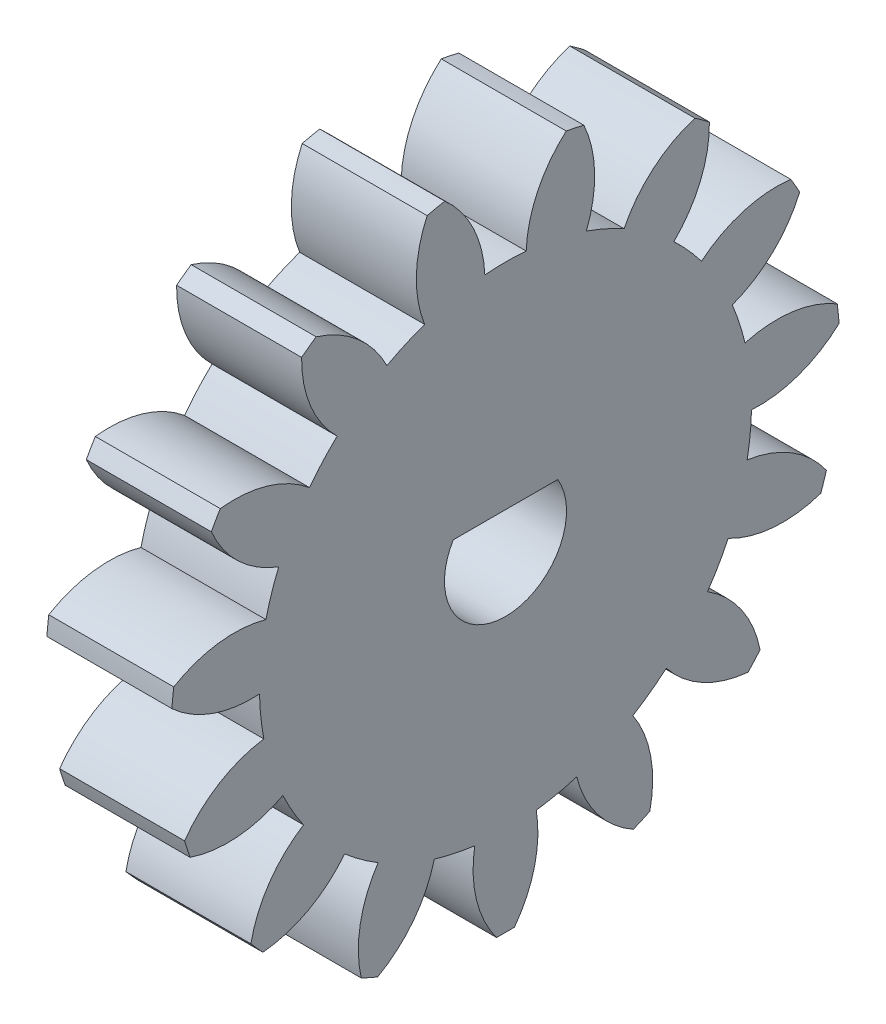
SolidWorks part; units mm, degrees
ref_plane "Plane1" through (0, 0, 0) normal (0, 0, 1) x (1, 0, 0)
ref_plane "Plane2" through (0, 0, 0) normal (0, 1, 0) x (1, 0, 0)
ref_plane "Plane3" through (0, 0, 0) normal (1, 0, 0) x (0, 0, -1)
sketch "HoldingSke" plane through (0, 0, 0) normal (0, 1, 0) x (1, 0, 0)
  line L0 (0, 0) -> (0.483, -0.1294)
  line L1 (-15, 0) -> (100, 0) construction
  line L2 (0, 0) -> (-2.1039, 2.3779)
  line L3 (0, 0) -> (-11.863, 4.5341)
  line L4 (0, 0) -> (8.3417, 2.2352)
  line L5 (0, 0) -> (-46.8476, -17.4728)
  line L6 (0, 0) -> (-5.2639, -3.5516)
  line L7 (-2.1039, 2.3779) -> (8.6586, 51.2059)
  line L8 (-76.2, 54.61) -> (-76.1, 54.61)
  line L9 (-71.009, 38.7566) -> (-53.1078, 45.2721)
  line L10 (-76.2, 71.12) -> (104.1128, 71.12)
  line L11 (0, 0) -> (-6.35, 0)
  line L12 (-76.2, 101.6) -> (-76.133, 101.6)
  line L13 (24.9733, 27.94) -> (52.9518, 28.4284)
  line L14 (24.9733, 27.94) -> (24.9743, 27.94)
  line L15 (24.9733, 27.94) -> (100.4006, 29.5858)
  line L16 (-63.627, -2) -> (-12.827, -2)
  circle A0 centre (0, 0) radius 0.4
  circle A1 centre (0, 0) radius 12.499
  circle A2 centre (0, 0) radius 37.5
  circle A3 centre (0, 0) radius 0.4
  dimension "MHD" = 24.998
  dimension "Hub_dia" = 75
  dimension "Bore" = 0.8
  dimension "MBD" = 0.8
  dimension "Num_teeth" = 15
  dimension "Pitch" = 0.5
  dimension "Overall_len" = 50
  dimension "Show_teeth" = 15
  dimension "Thickness" = 6.35
  dimension "OAL" = 50.0001
  dimension "T_dim" = 0.1
  dimension "Ap" = 20
  dimension "H" = 19.05
  dimension "Pitch_radius" = 180.3128
  dimension "Width" = 6.35
  dimension "Backlash" = 0.067
  dimension "Addendum_fac" = 1
  dimension "Dedendum_fac" = 1.25
  dimension "Clearance_fac" = 0.25
  dimension "Dedendum_add" = 0.001
  dimension "Module" = 2
sketch "BasProSke" plane through (0, 0, 0) normal (0, 1, 0) x (1, 0, 0)
  line L0 (-10, 0) -> (60, 0) construction
  line L1 (0, 0) -> (0, 17)
  line L2 (0, 0) -> (6.35, 0)
  line L3 (6.35, 0) -> (6.35, 17)
  line L4 (6.35, 17) -> (0, 17)
  dimension "Thickness" = 6.35
  dimension "Diameter" = 34
revolve "Base-Revolve" add sketch "BasProSke" angle 360 about L0
sketch "TooCutSke" plane through (0, 0, 0) normal (1, 0, 0) x (0, 0, -1)
  line L1 (0, 0) -> (0, 107) construction
  line L2 (0, 0) -> (-1.6851, 14.905) construction
  line L3 (0, 0) -> (-6.2081, 29.2069) construction
  line L4 (-1.6851, 14.905) -> (-3.1041, 14.6034) construction
  arc A0 (1.0501, 12.4548) -> (-1.0501, 12.4548) centre (0, 0) ccw
  arc A1 (3.1109, 16.7388) -> (-3.1109, 16.7388) centre (0, 0) ccw
  circle A2 centre (0, 0) radius 15 construction
  circle A3 centre (0, 0) radius 14.0954 construction
  arc A4 (-1.0501, 12.4548) -> (-3.1109, 16.7388) centre (-7.045, 12.2085) ccw
  arc A5 (3.1109, 16.7388) -> (1.0501, 12.4548) centre (7.045, 12.2085) ccw
  dimension "Root_dia" = 24.998
  dimension "Overcut_dia" = 34.0508
  dimension "Pitch_dia" = 30
  dimension "Base_dia" = 28.1908
  dimension "Flank_rad" = 6
  dimension "Half_ang" = 12
  dimension "Half_CT" = 1.4507
extrude "ToothCut" cut sketch "TooCutSke" along normal through all
fillet "Breaks" [suppressed] radius 0.04
fillet "RootFillets" [suppressed] radius 0.501
pattern_circular "TeethCuts" count 15 every 24 about axis through (-10, 0, 0) along (1, 0, 0) of "ToothCut", "RootFillets", "Breaks"
sketch "HubNeaOneSke" plane through (0, 0, 0) normal (-1, 0, 0) x (0, 0, 1)
  circle A0 centre (0, 0) radius 12.499
  dimension "Diameter" = 24.998
extrude "HubNearOne" [suppressed] add sketch "HubNeaOneSke" along normal blind 43.6501
sketch "HubNeaBotSke" plane through (0, 0, 0) normal (-1, 0, 0) x (0, 0, 1)
  circle A0 centre (0, 0) radius 12.499
  dimension "Diameter" = 24.998
extrude "HubNearBoth" [suppressed] add sketch "HubNeaBotSke" along normal blind 21.825
ref_plane "FarPln" through (6.35, 0, 0) normal (1, 0, 0) x (0, 0, -1)
sketch "HubFarSke" plane through (6.35, 0, 0) normal (1, 0, 0) x (0, 0, -1)
  circle A0 centre (0, 0) radius 12.499
  dimension "Diameter" = 24.998
extrude "HubFar" [suppressed] add sketch "HubFarSke" along normal blind 21.825
sketch "BorSke" plane through (0, 0, 0) normal (1, 0, 0) x (0, 0, -1)
  circle A0 centre (0, 0) radius 0.4
  dimension "Diameter" = 0.8
extrude "Bore" cut sketch "BorSke" along normal mid plane 100.0001
sketch "KeySke" plane through (0, 0, 0) normal (1, 0, 0) x (0, 0, -1)
  line L0 (-0.05, 0) -> (-0.05, 0.5)
  line L1 (-0.05, 0.5) -> (0.05, 0.5)
  line L2 (0.05, 0.5) -> (0.05, 0)
  line L3 (0, 0) -> (0, 34) construction
  line L4 (-0.05, 0) -> (0.05, 0)
  dimension "Offset" = 0.5
  dimension "Width" = 0.1
extrude "Keyway" [suppressed] cut sketch "KeySke" along normal mid plane 100.0001
pattern_circular "Keyway2" [suppressed] count 2 every 90 about axis through (-10, 0, 0) along (1, 0, 0)
sketch "Sketch1" plane through (6.35, 0, 0) normal (1, 0, 0) x (0, 0, -1)
  line L0 (-2.6552, 1.6) -> (2.6552, 1.6)
  circle A0 centre (0, 0) radius 3.1
  dimension "D1" = 6.2
  dimension "D2" = 1.6
extrude "Cut-Extrude1" cut sketch "Sketch1" against normal blind 10 contours L0 A0
equation "' \"Module@HoldingSke\" = 6.35"
equation "' \"Num_teeth@HoldingSke\" = 12"
equation "' \"Ap@HoldingSke\" =  20"
equation "' \"Ap@HoldingSke\" = 20"
equation "' \"Width@HoldingSke\" = 0.5 * 25.4"
equation "' \"Hub_dia@HoldingSke\"= 1 * 25.4"
equation "' \"Hub_dia@HoldingSke\" = 1 * 25.4"
equation "' \"Overall_len@HoldingSke\" = 1.0 * 25.4"
equation "' \"Bore@HoldingSke\" = 0.75 * 25.4"
equation "' \"T_dim@HoldingSke\" = 0.1 * 25.4"
equation "' \"Width@KeySke\" = 0.25 * 25.4"
equation "' \"Show_teeth@HoldingSke\" = 13"
equation "' \"Backlash@HoldingSke\" = 0.009 * 25.4"
equation "' \"Addendum_fac@HoldingSke\" = 1.0"
equation "' \"Dedendum_fac@HoldingSke\" = 1.25"
equation "' \"Dedendum_add@HoldingSke\" = 0.00005 * 25.4"
equation "' \"Clearance_fac@HoldingSke\" = 0.25"
equation "\"Pitch@HoldingSke\" = 1 / \"Module@HoldingSke\""
equation "\"Overcut_dia@TooCutSke\" = (\"Num_teeth@HoldingSke\" + 2 * \"Addendum_fac@HoldingSke\") / \"Pitch@HoldingSke\" + 0.002 * 25.4"
equation "\"Pitch_dia@TooCutSke\" = \"Num_teeth@HoldingSke\" / \"Pitch@HoldingSke\""
equation "\"Base_dia@TooCutSke\" = \"Num_teeth@HoldingSke\" / \"Pitch@HoldingSke\" * cos((\"Ap@HoldingSke\"  * 3.14159265 / 180))"
equation "\"Root_dia@TooCutSke\" = (\"Num_teeth@HoldingSke\" + 2) / \"Pitch@HoldingSke\" - 2 * (\"Addendum_fac@HoldingSke\" + \"Dedendum_fac@HoldingSke\") / \"Pitch@HoldingSke\" - \"Dedendum_add@HoldingSke\" * 2"
equation "\"Half_ang@TooCutSke\" = 180 / \"Num_teeth@HoldingSke\""
equation "\"Half_CT@TooCutSke\" = \"Num_teeth@HoldingSke\" / \"Pitch@HoldingSke\" * sin((3.14159265 / 2 / \"Num_teeth@HoldingSke\")) / 2 - 7 * \"Backlash@HoldingSke\" / 4"
equation "\"Flank_rad@TooCutSke\" = \"Num_teeth@HoldingSke\" / \"Pitch@HoldingSke\" / 5"
equation "\"Radius@RootFillets\" = \"Clearance_fac@HoldingSke\" / \"Pitch@HoldingSke\" + \"Dedendum_add@HoldingSke\""
equation "\"Break_rad@Breaks\" = 0.02 / \"Pitch@HoldingSke\""
equation "\"Thickness@HoldingSke\" = \"Width@HoldingSke\""
equation "\"OAL@HoldingSke\" = \"Thickness@HoldingSke\""
equation "\"MHD@HoldingSke\" = (\"Num_teeth@HoldingSke\" + 2) / \"Pitch@HoldingSke\" - 2 * (\"Addendum_fac@HoldingSke\" + \"Dedendum_fac@HoldingSke\")  / \"Pitch@HoldingSke\" - \"Dedendum_add@HoldingSke\" * 2"
equation "\"MBD@HoldingSke\" = (\"Num_teeth@HoldingSke\" + 2) / \"Pitch@HoldingSke\" - 2 * (\"Addendum_fac@HoldingSke\" + \"Dedendum_fac@HoldingSke\")  / \"Pitch@HoldingSke\" - \"Dedendum_add@HoldingSke\" * 2 - 0.002 * 25.4"
equation "\"MHD@HoldingSke\" = ((sgn( \"MHD@HoldingSke\" - \"Hub_dia@HoldingSke\" )-1)*( \"MHD@HoldingSke\" - \"Hub_dia@HoldingSke\" ))/-2+ \"Hub_dia@HoldingSke\""
equation "\"MBD@HoldingSke\" = ((sgn( \"MBD@HoldingSke\" - \"Bore@HoldingSke\" )-1)*( \"MBD@HoldingSke\" - \"Bore@HoldingSke\" ))/-2+ \"Bore@HoldingSke\""
equation "\"OAL@HoldingSke\" = ((sgn( \"OAL@HoldingSke\" - \"Overall_len@HoldingSke\" )+1)*( \"OAL@HoldingSke\" - \"Overall_len@HoldingSke\" ))/2 + \"Overall_len@HoldingSke\" + 0.000002 * 25.4"
equation "\"Num_teeth@TeethCuts\" = int( \"Show_teeth@HoldingSke\" ) + 1"
equation "\"Num_teeth@TeethCuts\" = ((sgn( \"Num_teeth@TeethCuts\" - \"Num_teeth@HoldingSke\" )-1)*( \"Num_teeth@TeethCuts\" - \"Num_teeth@HoldingSke\" ))/-2+ \"Num_teeth@HoldingSke\""
equation "\"Num_teeth@TeethCuts\" = ((sgn( \"Num_teeth@TeethCuts\" - 2.0)+1)*( \"Num_teeth@TeethCuts\" - 2.0))/2 +2.0"
equation "\"Angle@TeethCuts\" = 360.0 / \"Num_teeth@HoldingSke\""
equation "\"Diameter@BasProSke\" = (\"Num_teeth@HoldingSke\" + 2 * \"Addendum_fac@HoldingSke\") / \"Pitch@HoldingSke\""
equation "\"Thickness@BasProSke\"  = \"Thickness@HoldingSke\""
equation "' \"Fillet_rad@BasProSke\" =  \"Thickness@HoldingSke\" * 0.05"
equation "' \"Fillet_rad@BasProSke\" = \"Thickness@HoldingSke\" * 0.05"
equation "\"MHD@HoldingSke\" = ((sgn( \"MHD@HoldingSke\" - \"Root_dia@TooCutSke\" )-1)*( \"MHD@HoldingSke\" - \"Root_dia@TooCutSke\" ))/-2+ \"Root_dia@TooCutSke\""
equation "\"Diameter@HubNeaOneSke\" = \"MHD@HoldingSke\""
equation "\"Length@HubNearOne\" = \"OAL@HoldingSke\" - \"Thickness@BasProSke\""
equation "\"Diameter@HubNeaBotSke\" = \"MHD@HoldingSke\""
equation "\"Length@HubNearBoth\" = ( \"OAL@HoldingSke\" - \"Thickness@BasProSke\" ) / 2.0"
equation "\"Thickness@FarPln\" = \"Thickness@BasProSke\""
equation "\"Diameter@HubFarSke\" = \"MHD@HoldingSke\""
equation "\"Length@HubFar\" = ( \"OAL@HoldingSke\" - \"Thickness@BasProSke\" ) / 2.0"
equation "\"Diameter@BorSke\" = \"MBD@HoldingSke\""
equation "\"D1@Bore\" = \"OAL@HoldingSke\" * 2.0"
equation "\"D1@Keyway\" = \"OAL@HoldingSke\" * 2.0"
equation "\"Offset@KeySke\" = \"T_dim@HoldingSke\" + \"MBD@HoldingSke\" / 2.0"
equation "\"D2@Sketch1\"=4.5-\"D1@Sketch1\"/2 + 0.2"
